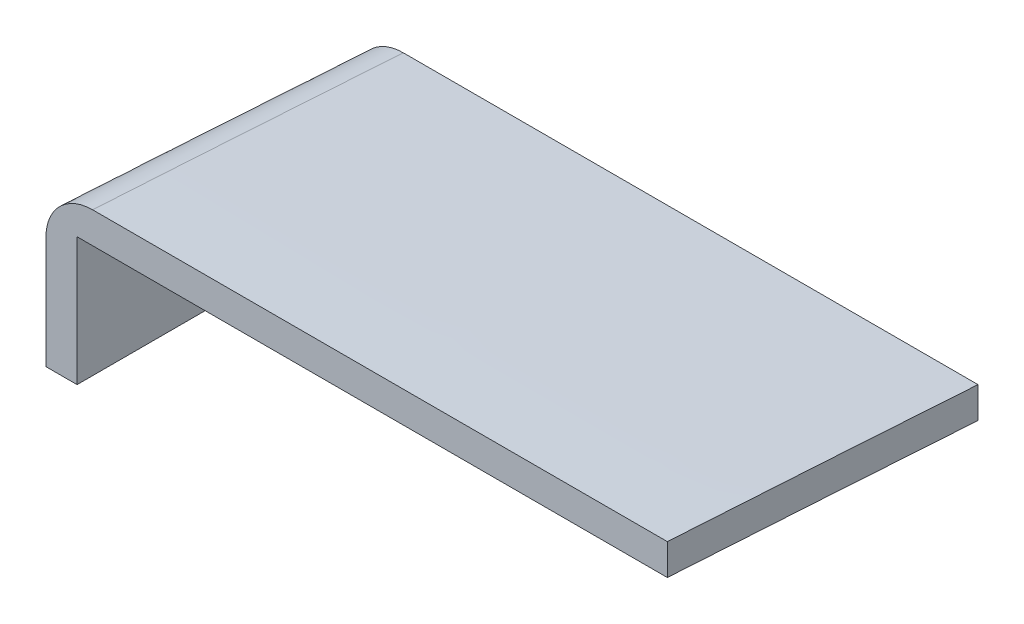
SolidWorks part; units mm, degrees
ref_plane "정면" through (0, 0, 0) normal (0, 0, 1) x (1, 0, 0)
ref_plane "윗면" through (0, 0, 0) normal (0, 1, 0) x (1, 0, 0)
ref_plane "우측면" through (0, 0, 0) normal (1, 0, 0) x (0, 0, -1)
sketch "스케치1" plane through (0, 0, 0) normal (0, 0, 1) x (1, 0, 0)
  line L1 (-40, 50) -> (40, 50)
  line L2 (-40, 50) -> (-40, -50)
  line L3 (-40, -50) -> (40, -50)
  line L4 (40, 50) -> (40, -50)
  line L5 (-40, 50) -> (40, -50) construction
  line L6 (-40, -50) -> (40, 50) construction
  point P0 (0, 0)
  dimension "D1" = 80
  dimension "D2" = 100
extrude "보스-돌출1" add sketch "스케치1" against normal blind 100
sketch "스케치2" plane through (40, 0, 0) normal (1, 0, 0) x (0, 0, -1)
  line L0 (100, -50) -> (100, 50) construction
  line L1 (0, 50) -> (80, 50)
  line L2 (0, 50) -> (0, -35)
  line L3 (0, -35) -> (80, -35)
  line L4 (80, 50) -> (80, -35)
  line L5 (100, -50) -> (0, -50) construction
  dimension "D1" = 20
  dimension "D2" = 15
extrude "컷-돌출1" cut sketch "스케치2" against normal blind 90
sketch "스케치5" plane through (40, 0, 0) normal (1, 0, 0) x (0, 0, -1)
  line L0 (0, -50) -> (0, -35) construction
  line L1 (100, 50) -> (80, 50) construction
  line L2 (96, 50) -> (80, 50)
  line L4 (80, 50) -> (80, -35)
  line L6 (80, -35) -> (0, -35)
  line L8 (80, 50) -> (80, -35)
  line L9 (80, -35) -> (0, -35)
  line L10 (0, -35) -> (0, -50)
  line L11 (0, -50) -> (100, -50)
  line L12 (100, -50) -> (100, 50)
  line L13 (100, 50) -> (80, 50)
  line L15 (80, -35) -> (0, -35)
  line L16 (0, -35) -> (0, -50)
  line L17 (0, -50) -> (100, -50)
  line L18 (100, -50) -> (100, 50)
  line L19 (100, 50) -> (80, 50)
  line L20 (80, 50) -> (80, -35)
  spline S0 degree 3 poles (0, -39.3767) (18.6089, -37.8138) (60.522, -41.4488) (82.6293, -41.815) (94.477, -29.9816) (72.3521, -11.4072) (96, 50) knots 0 0 0 0 0.361872 0.526262 0.755385 1 1 1 1
  dimension "D9" = 9.5231
  dimension "D2" = 22.8534
  dimension "D3" = 11
  dimension "D4" = 8.7853
  dimension "D5" = 36.2853
  dimension "D6" = 13.0435
  dimension "D7" = 22.021
  dimension "D8" = 20
  dimension "D10" = 16
  dimension "D11" = 4.3767
  dimension "D1" = 0
extrude "컷-돌출5" cut sketch "스케치5" against normal through all
shell "쉘2" thickness 2
fillet "필렛1" radius 3 1 edges at (0, 50, -96)
fillet "필렛2" radius 5 1 edges at (0, -39.3767, 0)
fillet "필렛3" radius 3 10 edges at (-40, -47.0329, 0) (-40, -40.6133, -1.3834) (-40, 50, -99.0322) (-40, 49.4694, -96.3609) (40, -47.0329, 0) (40, -40.6133, -1.3834) (40, 50, -99.0322) (40, 49.4694, -96.3609)
ref_plane "평면1" through (40, 47, -98.0645) normal (0, -0.9348, 0.3551) x (-1, 0, 0)
sketch "스케치6" plane through (0, 0, -100) normal (0, 0, -1) x (-1, 0, 0)
  line L0 (-40, -50) -> (-40, 47) construction
  line L1 (-40, -50) -> (-40, 47)
  line L2 (-40, 10) -> (40, 10)
  line L3 (40, 47) -> (40, -50) construction
  line L4 (0, 20.2731) -> (0, 42) construction
  line L5 (-11.9, 11.25) -> (-8.1, 11.25)
  line L6 (-11.9, 11.25) -> (-11.9, 8.75)
  line L7 (-11.9, 8.75) -> (-8.1, 8.75)
  line L8 (-8.1, 11.25) -> (-8.1, 8.75)
  line L9 (-11.9, 11.25) -> (-8.1, 8.75) construction
  line L10 (-11.9, 8.75) -> (-8.1, 11.25) construction
  line L11 (-37, 50) -> (37, 50) construction
  line L12 (11.9, 8.75) -> (8.1, 11.25) construction
  line L13 (11.9, 11.25) -> (8.1, 8.75) construction
  line L14 (8.1, 11.25) -> (8.1, 8.75)
  line L15 (11.9, 8.75) -> (8.1, 8.75)
  line L16 (11.9, 11.25) -> (11.9, 8.75)
  line L17 (11.9, 11.25) -> (8.1, 11.25)
  point P7 (-10, 10)
  point P19 (10, 10)
  dimension "D1" = 3.8
  dimension "D2" = 2.5
  dimension "D3" = 10
  dimension "D4" = 40
extrude "컷-돌출6" cut sketch "스케치6" against normal blind 85 contours L8 L5 L6 L2 | L8 L2 L6 L7 | L16 L2 L14 L15
sketch "스케치8" plane through (0, 50, 0) normal (0, 1, 0) x (1, 0, 0)
  line L0 (-37, 81.3983) -> (-40, 71.8589)
  line L1 (-40, 96) -> (-40, 0) construction
  line L2 (-40, 71.8589) -> (40, 71.8589)
  line L3 (40, 0) -> (40, 96) construction
  line L4 (0, 76.7018) -> (0, 80.7018) construction
  line L5 (-22.5, 71.8589) -> (-17.5, 71.8589)
  line L6 (-22.5, 71.8589) -> (-22.5, 66.8589)
  line L7 (-22.5, 66.8589) -> (-17.5, 66.8589)
  line L8 (-17.5, 71.8589) -> (-17.5, 66.8589)
  line L9 (-22.5, 71.8589) -> (-17.5, 66.8589) construction
  line L10 (-22.5, 66.8589) -> (-17.5, 71.8589) construction
  line L12 (22.5, 66.8589) -> (17.5, 71.8589) construction
  line L13 (22.5, 71.8589) -> (17.5, 66.8589) construction
  line L14 (17.5, 71.8589) -> (17.5, 66.8589)
  line L15 (22.5, 66.8589) -> (17.5, 66.8589)
  line L16 (22.5, 71.8589) -> (22.5, 66.8589)
  line L17 (22.5, 71.8589) -> (17.5, 71.8589)
  point P5 (-20, 69.3589)
  point P14 (0, 71.8589)
  point P20 (20, 69.3589)
  dimension "D1" = 10
  dimension "D2" = 5
  dimension "D3" = 5
  dimension "D4" = 20
extrude "컷-돌출7" cut sketch "스케치8" against normal blind 100 contours L8 L2 L6 L7 | L8 L5 L6 L2 | L16 L17 L14 L2 | L16 L2 L14 L15
sketch "스케치11" plane through (0, 0, -100) normal (0, 0, -1) x (-1, 0, 0)
  line L1 (-22.3234, 3.6269) -> (45.6766, 3.6269) construction
  line L2 (0, 45.5744) -> (0, 67.3013) construction
  line L9 (-37, 50) -> (37, 50) construction
  line L10 (-11, 4.1269) -> (-9, 4.1269)
  line L15 (-11, 4.1269) -> (-11, 3.1269)
  line L16 (-11, 3.1269) -> (-9, 3.1269)
  line L17 (-9, 4.1269) -> (-9, 3.1269)
  line L18 (-11, 4.1269) -> (-9, 3.1269) construction
  line L19 (-11, 3.1269) -> (-9, 4.1269) construction
  line L20 (11, 3.1269) -> (9, 3.1269)
  line L21 (11, 4.1269) -> (11, 3.1269)
  line L22 (11, 4.1269) -> (9, 4.1269)
  line L23 (9, 4.1269) -> (9, 3.1269)
  point P2 (-10, 3.6269)
  dimension "D2" = 2
  dimension "D3" = 1
  dimension "D1" = 46.3731
  dimension "D4" = 10
extrude "컷-돌출8" cut sketch "스케치11" against normal through all
scale "축척1" bodies to scale 119 scale about origin uniform scaling yes scale factor 5
sketch "스케치12" plane through (0, 0, 0) normal (0, 0, 1) x (1, 0, 0)
  line L0 (200, -222.4272) -> (200, 235) construction
  line L1 (-200, 250) -> (200, 250)
  line L2 (-200, 250) -> (-200, -50)
  line L3 (-200, -50) -> (200, -50)
  line L4 (200, 250) -> (200, -50)
  line L5 (-185, 250) -> (185, 250) construction
  line L6 (-200, 235) -> (-200, -222.4272) construction
  line L7 (0, -50) -> (0, -250)
  line L8 (-185, -250) -> (185, -250) construction
  line L9 (0, -250) -> (200, -250)
  line L11 (200, -250) -> (200, -50)
  line L12 (-200, -50) -> (-200, -250)
  line L13 (-200, -250) -> (0, -250)
  line M7 (185, -220.3291) -> (-185, -220.3291)
  line M9 (-185, -250) -> (185, -250)
  line M10 (185, -250) -> (185, -220.3291)
  dimension "D1" = 200
extrude "컷-돌출14" cut sketch "스케치12" against normal through all contours L4 L1 L2 L3 | L9 L11 L3 L7 M7 M10 | L7 M7 M9 M10
sketch "스케치17" plane through (0, -250, 0) normal (0, -1, 0) x (1, 0, 0)
  line L0 (-200, -500) -> (-200, -15) construction
  line L1 (-200, -200) -> (0, -200)
  line L2 (-200, -200) -> (-200, 0)
  line L3 (-200, 0) -> (0, 0)
  line L4 (0, -200) -> (0, 0)
  line L6 (-200, -300) -> (0, -300)
  line L7 (-200, -300) -> (-200, -500)
  line L8 (-200, -500) -> (0, -500)
  line L9 (0, -300) -> (0, -500)
  dimension "D1" = 100
  dimension "D2" = 200
extrude "컷-돌출15" cut sketch "스케치17" against normal through all and the other way through all contours L2 L1 L4 L3 | L7 L6 L9 L8
